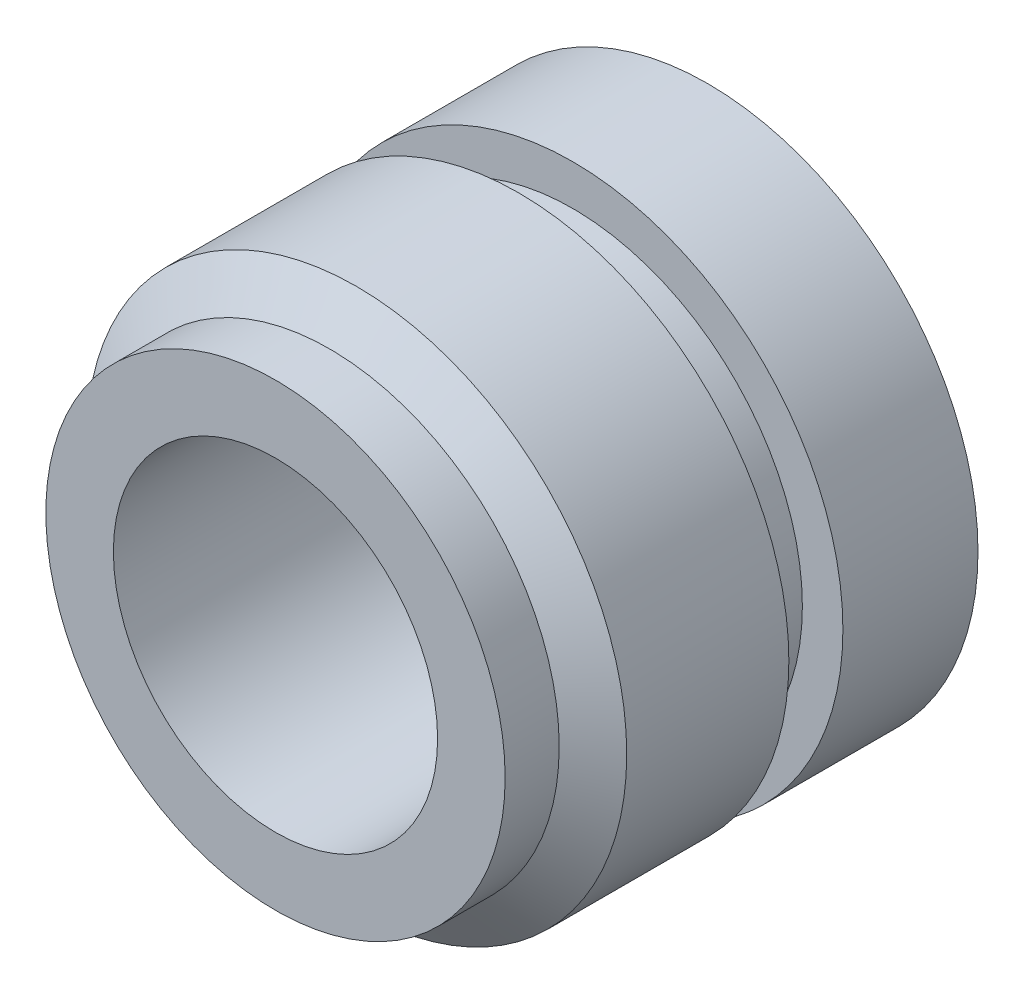
SolidWorks part; units mm, degrees
material "Brass"
ref_plane "Front Plane" through (0, 0, 0) normal (0, 0, 1) x (1, 0, 0)
ref_plane "Top Plane" through (0, 0, 0) normal (0, 1, 0) x (1, 0, 0)
ref_plane "Right Plane" through (0, 0, 0) normal (1, 0, 0) x (0, 0, -1)
sketch "Sketch1" plane through (0, 0, 0) normal (0, 0, 1) x (1, 0, 0)
  circle A0 centre (0, 0) radius 2.5
  dimension "D1" = 5
extrude "Boss-Extrude1" add sketch "Sketch1" along normal blind 4
sketch "Sketch2" plane through (0, 0, 0) normal (0, 1, 0) x (1, 0, 0)
  line L0 (-2.125, -4) -> (-3, -4)
  line L1 (-2.5, 0) -> (-2.5, -1.25)
  line L2 (-2.5, 0) -> (-2.5, -4) construction
  line L3 (-2.5, -1.25) -> (-2.125, -1.25)
  line L4 (-2.125, -1.25) -> (-2.125, -1.75)
  line L5 (-2.125, -1.75) -> (-2.5, -1.75)
  line L6 (-2.5, -1.75) -> (-2.5, -3.25)
  line L7 (-2.5, -3.25) -> (-2.125, -3.5)
  line L8 (-2.125, -3.5) -> (-2.125, -4)
  line L9 (-2.5, -4) -> (2.5, -4) construction
  line L10 (-3, -4) -> (-3, 0)
  line L11 (-3, 0) -> (-2.5, 0)
  point P0 (-2.125, -3.4567)
  dimension "D1" = 0.375
  dimension "D2" = 0.375
  dimension "D3" = 1.25
  dimension "D4" = 0.5
  dimension "D5" = 1.5
  dimension "D6" = 0.5
  dimension "D7" = 0.5
ref_axis "Axis1" through (0, 0, 4) along (0, 0, -1)
revolve "Cut-Revolve1" cut sketch "Sketch2" angle 360 about axis through (0, 0, 4) along (0, 0, -1)
sketch "Sketch3" plane through (0, 0, 0) normal (0, 0, -1) x (-1, 0, 0)
  circle A0 centre (0, 0) radius 1.5
  dimension "D1" = 3
extrude "Cut-Extrude1" cut sketch "Sketch3" against normal blind 5
chamfer "Chamfer1" distance 0.1 angle 45 1 edges at (-1.5, 0, 0)
